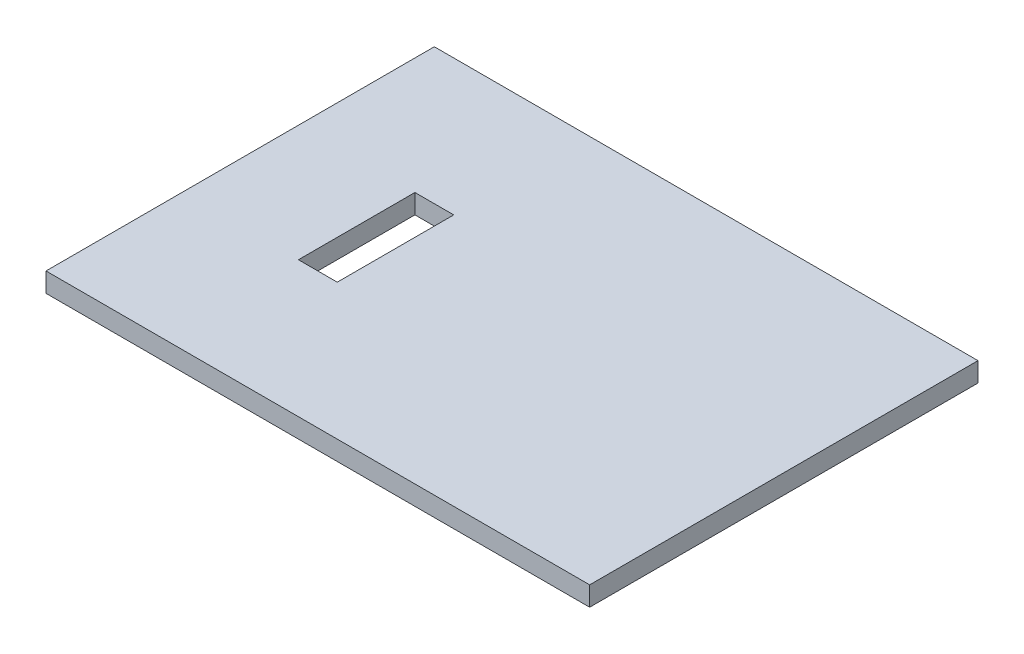
SolidWorks part; units mm, degrees
ref_plane "Front Plane" through (0, 0, 0) normal (0, 0, 1) x (1, 0, 0)
ref_plane "Top Plane" through (0, 0, 0) normal (0, 1, 0) x (1, 0, 0)
ref_plane "Right Plane" through (0, 0, 0) normal (1, 0, 0) x (0, 0, -1)
sketch "Sketch1" plane through (0, 0, 0) normal (0, 1, 0) x (1, 0, 0)
  line L1 (35, -25) -> (-35, -25)
  line L2 (35, -25) -> (35, 25)
  line L3 (35, 25) -> (-35, 25)
  line L4 (-35, -25) -> (-35, 25)
  line L5 (35, -25) -> (-35, 25) construction
  line L6 (35, 25) -> (-35, -25) construction
  point P0 (0, 0)
  dimension "D1" = 70
  dimension "D2" = 50
extrude "Boss-Extrude1" add sketch "Sketch1" along normal blind 2.5
sketch "Sketch2" plane through (0, 2.5, 0) normal (0, 1, 0) x (1, 0, 0)
  line L1 (-15, -7.5) -> (-20, -7.5)
  line L2 (-15, -7.5) -> (-15, 7.5)
  line L3 (-15, 7.5) -> (-20, 7.5)
  line L4 (-20, -7.5) -> (-20, 7.5)
  line L5 (-15, -7.5) -> (-20, 7.5) construction
  line L6 (-15, 7.5) -> (-20, -7.5) construction
  point P0 (-17.5, 0)
  point P5 (-17.5, 1.9177)
  point P7 (0, 0)
  dimension "D1" = 15
  dimension "D2" = 5
  dimension "D3" = 17.5
extrude "Cut-Extrude1" cut sketch "Sketch2" against normal blind 2.5
